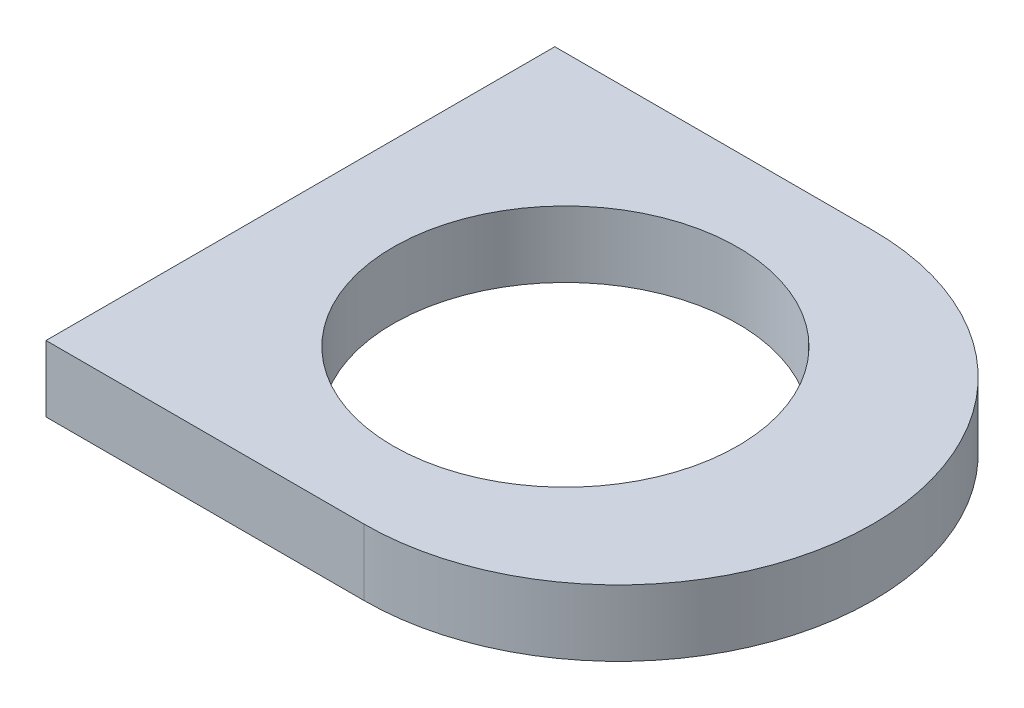
SolidWorks part; units mm, degrees
ref_plane "Front Plane" through (0, 0, 0) normal (0, 0, 1) x (1, 0, 0)
ref_plane "Top Plane" through (0, 0, 0) normal (0, 1, 0) x (1, 0, 0)
ref_plane "Right Plane" through (0, 0, 0) normal (1, 0, 0) x (0, 0, -1)
sketch "Sketch1" plane through (0, 0, 0) normal (0, 1, 0) x (1, 0, 0)
  line L0 (0, 85.2368) -> (0, -86.7967) construction
  line L1 (-112.261, 0) -> (142.0009, 0) construction
  line L2 (-50, 48) -> (-50, -48)
  line L3 (-50, 48) -> (0, 48)
  line L4 (-50, -48) -> (0, -48)
  line L5 (10, 85.2368) -> (10, -86.7967) construction
  line L9 (0, 48) -> (10, 48)
  line L10 (0, -48) -> (10, -48)
  line L11 (0, 40) -> (10, 40)
  line L12 (-42, 40) -> (0, 40)
  line L13 (-42, 40) -> (-42, -40)
  line L14 (-42, -40) -> (0, -40)
  line L15 (0, -40) -> (10, -40)
  circle A0 centre (0, 0) radius 32.5
  arc A1 (10, -48) -> (10, 48) centre (10, 0) ccw
  arc A2 (10, -40) -> (10, 40) centre (10, 0) ccw
  point P7 (-50, 0)
  dimension "D3" = 65
  dimension "D7" = 8
  dimension "D1" = 96
  dimension "D2" = 50
  dimension "D4" = 60
extrude "Boss-Extrude1" add sketch "Sketch1" along normal blind 12.5 contours L15 A2 L11 L12 L13 L14 A0 | L10 A1 L9 L3 L2 L4 A2 L15 L14 L13 L12 L11
